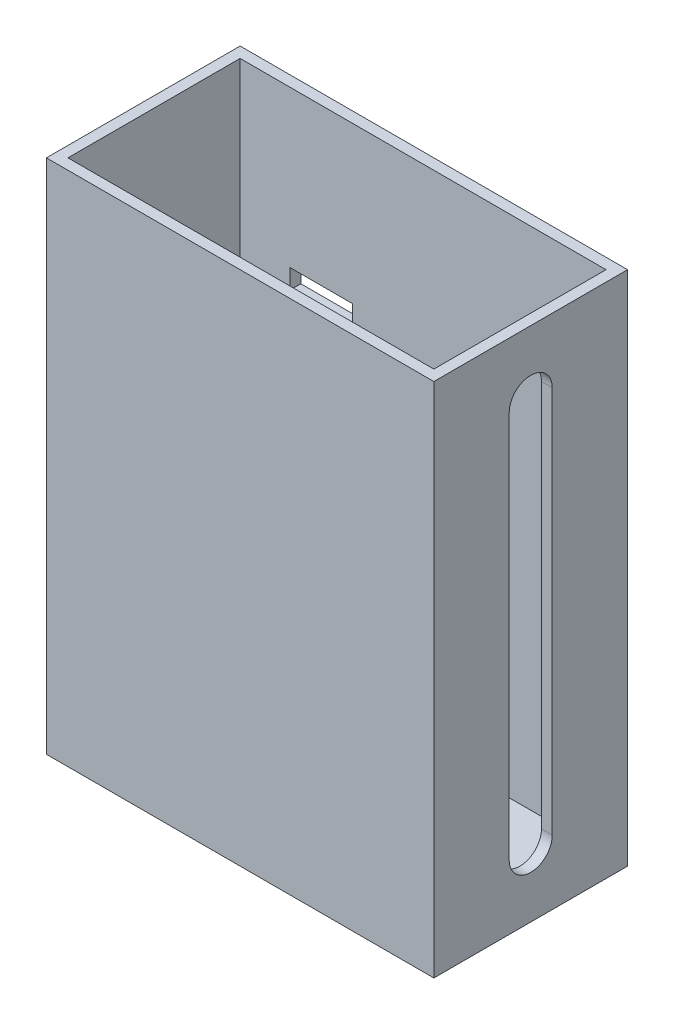
SolidWorks part; units mm, degrees
ref_plane "Front Plane" through (0, 0, 0) normal (0, 0, 1) x (1, 0, 0)
ref_plane "Top Plane" through (0, 0, 0) normal (0, 1, 0) x (1, 0, 0)
ref_plane "Right Plane" through (0, 0, 0) normal (1, 0, 0) x (0, 0, -1)
sketch "Sketch1" plane through (0, 0, 0) normal (0, 1, 0) x (1, 0, 0)
  line L1 (-228.6, 114.3) -> (228.6, 114.3)
  line L2 (-228.6, 114.3) -> (-228.6, -114.3)
  line L3 (-228.6, -114.3) -> (228.6, -114.3)
  line L4 (228.6, 114.3) -> (228.6, -114.3)
  line L5 (-228.6, 114.3) -> (228.6, -114.3) construction
  line L6 (-228.6, -114.3) -> (228.6, 114.3) construction
  point P0 (0, 0)
  dimension "D1" = 228.6
  dimension "D2" = 457.2
extrude "Boss-Extrude1" add sketch "Sketch1" along normal blind 609.6
shell "Shell2" thickness 12.7
sketch "Sketch3" plane through (228.6, 0, 0) normal (1, 0, 0) x (0, 0, -1)
  line L0 (0, 76.2) -> (0, 533.4) construction
  line L3 (0, 0) -> (0, 609.6) construction
  line L4 (-114.3, 609.6) -> (114.3, 609.6) construction
  line L5 (-25.4, 76.2) -> (-25.4, 533.4)
  line L6 (25.4, 76.2) -> (25.4, 533.4)
  arc A2 (-25.4, 76.2) -> (25.4, 76.2) centre (0, 76.2) ccw
  arc A3 (25.4, 533.4) -> (-25.4, 533.4) centre (0, 533.4) ccw
  point P2 (0, 304.8)
extrude "Cut-Extrude2" cut sketch "Sketch3" against normal up to next
sketch "Sketch4" plane through (0, 0, -114.3) normal (0, 0, -1) x (-1, 0, 0)
  line L1 (156.9816, 425.277) -> (83.3216, 425.277)
  line L2 (156.9816, 425.277) -> (156.9816, 402.417)
  line L3 (156.9816, 402.417) -> (83.3216, 402.417)
  line L4 (83.3216, 425.277) -> (83.3216, 402.417)
  line L5 (120.1516, 402.417) -> (120.1516, 425.277)
  line L6 (156.9816, 413.847) -> (83.3216, 413.847)
  line L7 (93.5736, 369.1154) -> (157.0736, 369.1154)
  line L8 (93.5736, 369.1154) -> (93.5736, 300.5354)
  line L9 (93.5736, 300.5354) -> (157.0736, 300.5354)
  line L10 (157.0736, 369.1154) -> (157.0736, 300.5354)
  line L11 (125.3236, 300.5354) -> (125.3236, 369.1154)
  line L12 (93.5736, 334.8254) -> (157.0736, 334.8254)
  point P0 (120.1516, 413.847)
  point P4 (125.3236, 334.8254)
extrude "Cut-Extrude3" cut sketch "Sketch4" against normal up to next contours L8 L12 L11 L7 | L12 L8 L9 L11 | L12 L11 L9 L10 | L11 L12 L10 L7 | L6 L2 L1 L5 | L2 L6 L5 L3 | L6 L5 L1 L4 | L5 L6 L4 L3
sketch "Sketch6" plane through (0, 0, -114.3) normal (0, 0, -1) x (-1, 0, 0)
  line L0 (-228.6, 520.5463) -> (-63.5, 520.5463) construction
  line L1 (-228.6, 609.6) -> (-228.6, 0) construction
  line L2 (-111.8984, 609.6) -> (-111.8984, 520.7)
  line L3 (-228.6, 609.6) -> (228.6, 609.6) construction
  circle A2 centre (-63.5, 520.5463) radius 2.794
  dimension "rodhole Sprocket" = 5.588
sketch "Sketch11" plane through (-228.6, 0, 0) normal (-1, 0, 0) x (0, 0, 1)
  line L0 (-65.3852, 24.1159) -> (-88.1132, 24.1159) construction
  line L1 (-65.3852, 17.7659) -> (-88.1132, 17.7659)
  line L2 (-65.3852, 30.4659) -> (-88.1132, 30.4659)
  arc A0 (-65.3852, 17.7659) -> (-65.3852, 30.4659) centre (-65.3852, 24.1159) ccw
  arc A1 (-88.1132, 30.4659) -> (-88.1132, 17.7659) centre (-88.1132, 24.1159) ccw
  point P2 (-76.7492, 24.1159)
extrude "Cut-Extrude17" cut sketch "Sketch11" against normal blind 55.88 contours L2 A1 L1 A0
ref_plane "Plane12" through (-228.6, 30.4659, -65.3852) normal (0, 0, -1) x (-1, 0, 0)
